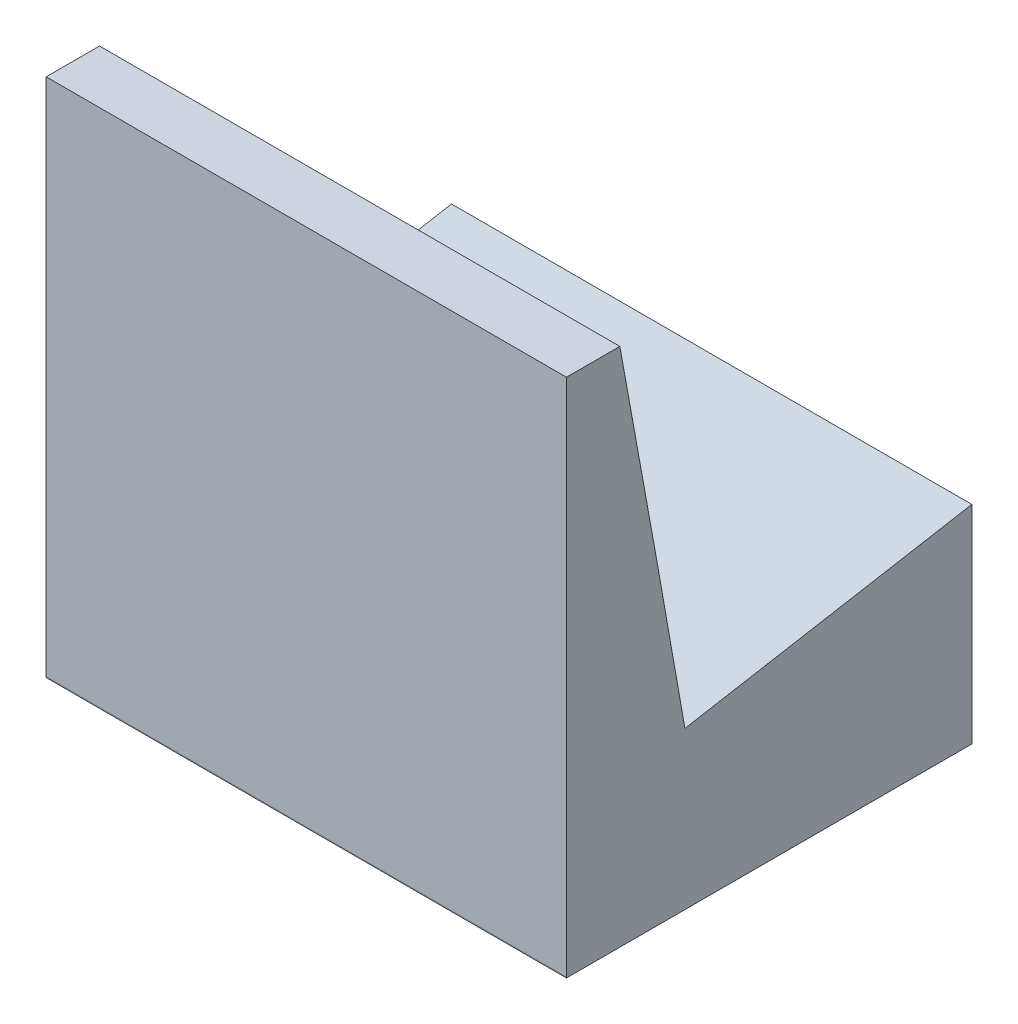
SolidWorks part; units mm, degrees
ref_plane "Front Plane" through (0, 0, 0) normal (0, 0, 1) x (1, 0, 0)
ref_plane "Top Plane" through (0, 0, 0) normal (0, 1, 0) x (1, 0, 0)
ref_plane "Right Plane" through (0, 0, 0) normal (1, 0, 0) x (0, 0, -1)
sketch "Sketch1" plane through (0, 0, 0) normal (0, 1, 0) x (1, 0, 0)
  line L1 (-39, 39) -> (39, 39)
  line L2 (-39, 39) -> (-39, -39)
  line L3 (-39, -39) -> (39, -39)
  line L4 (39, 39) -> (39, -39)
  line L5 (-39, 39) -> (39, -39) construction
  line L6 (-39, -39) -> (39, 39) construction
  point P0 (0, 0)
  dimension "D1" = 78
  dimension "D2" = 78
extrude "Boss-Extrude1" add sketch "Sketch1" along normal blind 78 contours L2 L1 L4 L3
sketch "Sketch2" plane through (39, 0, 0) normal (1, 0, 0) x (0, 0, -1)
  line L0 (-9.8959, 78) -> (-9.8959, 0) construction
  line L1 (39, 78) -> (-39, 78) construction
  line L2 (39, 0) -> (-39, 0) construction
  line L3 (-9.8959, 78) -> (-9.8959, 31.1068) construction
  line L4 (39, 0) -> (39, 31.1068)
  line L5 (39, 78) -> (39, 0) construction
  line L6 (39, 31.1068) -> (-4.0121, 23.5226)
  line L7 (-4.0121, 23.5226) -> (-8.3784, 48.2851)
  line L8 (-8.3784, 48.2851) -> (-13.7673, 78)
  line L9 (-13.7673, 78) -> (-21.7673, 78)
  line L10 (-13.7673, 78) -> (-13.7673, 0.1417)
  line L11 (-21.7673, 78) -> (-21.7673, 0.1417)
  line L12 (-13.7673, 0.1417) -> (-21.7673, 0.1417)
  line L13 (-13.7673, 78) -> (39, 78)
  line L14 (39, 78) -> (39, 31.1068)
  line L15 (-39, 0) -> (-39, 78)
  line L16 (-39, 78) -> (-21.7673, 78)
  line L17 (-21.7673, 0.1417) -> (-39, 0)
  line M6 (39, 0) -> (39, 78)
  line M7 (39, 78) -> (-39, 78)
  line M8 (-39, 78) -> (-39, 0)
  dimension "D1" = 80
  dimension "D2" = 10
  dimension "D3" = 8
extrude "Cut-Extrude2" cut sketch "Sketch2" against normal through all contours L17 L11 M7 M8 | L8 L7 L6 M6 M7
sketch "Sketch3" plane through (0, 0.3208, 0.0026) normal (0, 1, 0.0082) x (1, 0, 0)
  line L1 (-39, -38.9987) -> (39, -38.9987)
  line L2 (-39, -38.9987) -> (-39, -21.7654)
  line L3 (-39, -21.7654) -> (39, -21.7654)
  line L4 (39, -38.9987) -> (39, -21.7654)
extrude "Cut-Extrude3" cut sketch "Sketch3" against normal through all contours L2 L1 L4 L3
